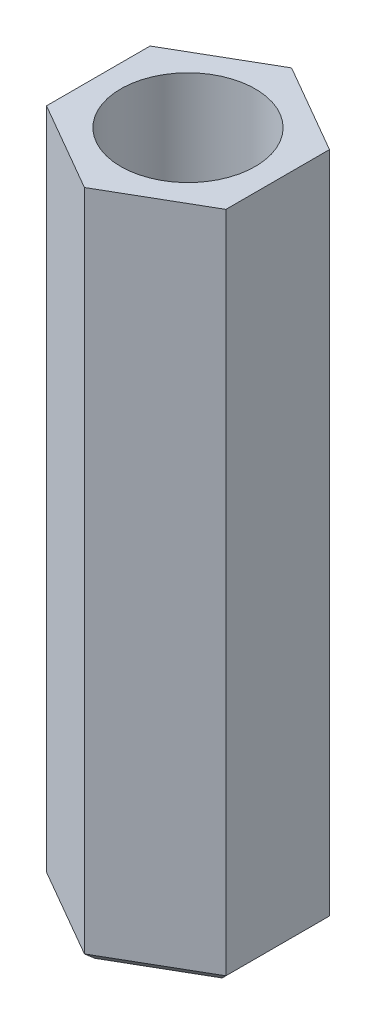
SolidWorks part; units mm, degrees
ref_plane "Plan de face" through (0, 0, 0) normal (0, 0, 1) x (1, 0, 0)
ref_plane "Plan de dessus" through (0, 0, 0) normal (0, 1, 0) x (1, 0, 0)
ref_plane "Plan de droite" through (0, 0, 0) normal (1, 0, 0) x (0, 0, -1)
sketch "Esquisse1" plane through (0, 0, 0) normal (0, 1, 0) x (1, 0, 0)
  line L0 (0, 2.3094) -> (0, 0) construction
  line L1 (0, -2.3094) -> (2, -1.1547)
  line L2 (2, -1.1547) -> (2, 1.1547)
  line L3 (2, 1.1547) -> (0, 2.3094)
  line L4 (0, 2.3094) -> (-2, 1.1547)
  line L5 (-2, 1.1547) -> (-2, -1.1547)
  line L6 (-2, -1.1547) -> (0, -2.3094)
  circle A0 centre (0, 0) radius 2 construction
  circle A1 centre (0, 0) radius 1.5
  dimension "D2" = 3
  dimension "D1" = 4
extrude "Boss.-Extru.1" add sketch "Esquisse1" along normal blind 15
chamfer "Chanfrein1" distance 0.2 angle 45 7 edges at (0, 0, 1.5) (1, 0, 1.7321) (2, 0, 0) (1, 0, -1.7321) (-1, 0, -1.7321) (-2, 0, 0) (-1, 0, 1.7321)
